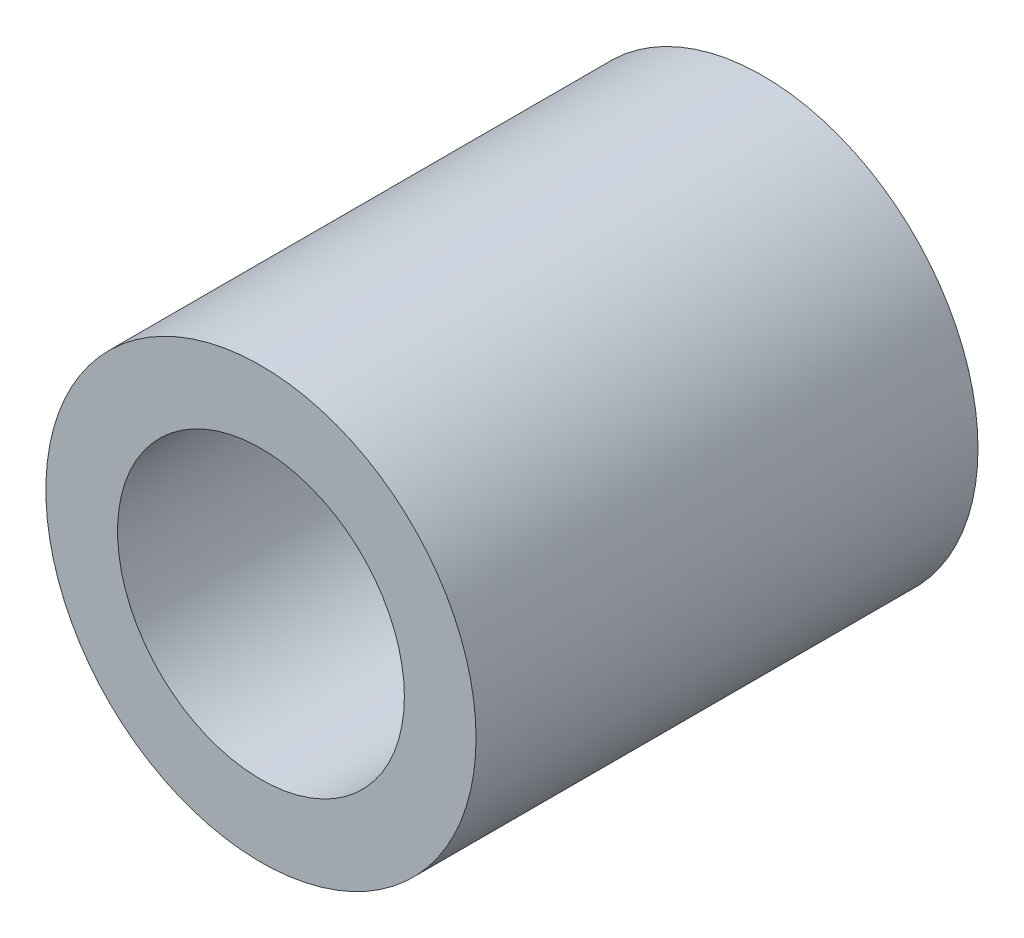
SolidWorks part; units mm, degrees
ref_plane "Front" through (0, 0, 0) normal (0, 0, 1) x (1, 0, 0)
ref_plane "Top" through (0, 0, 0) normal (0, 1, 0) x (1, 0, 0)
ref_plane "Right" through (0, 0, 0) normal (1, 0, 0) x (0, 0, -1)
sketch "Esquisse1" plane through (0, 0, 0) normal (0, 0, 1) x (1, 0, 0)
  circle A0 centre (0, 0) radius 3
  dimension "D1" = 6
extrude "Extru.-Mince1" add sketch "Esquisse1" along normal blind 7 thin thin type one direction reverse wall 1
